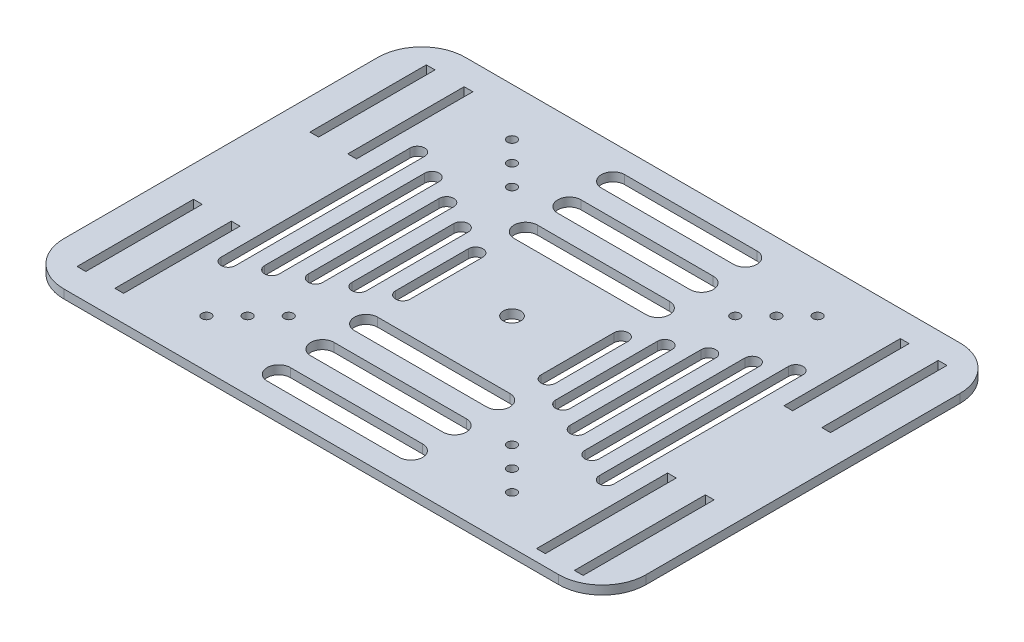
SolidWorks part; units mm, degrees
ref_plane "前视基准面" through (0, 0, 0) normal (0, 0, 1) x (1, 0, 0)
ref_plane "上视基准面" through (0, 0, 0) normal (0, 1, 0) x (1, 0, 0)
ref_plane "右视基准面" through (0, 0, 0) normal (1, 0, 0) x (0, 0, -1)
sketch "草图2" plane through (0, 0, 0) normal (0, 1, 0) x (1, 0, 0)
  line L0 (100, 100) -> (100, -100)
  line L1 (100, 100) -> (-100, 100) construction
  line L2 (100, -100) -> (-100, -100) construction
  line L3 (-100, 100) -> (-100, -100)
  line L4 (100, 100) -> (-100, -100) construction
  line L5 (100, -100) -> (-100, 100) construction
  line L6 (0, 65) -> (0, -65) construction
  line L7 (-68.9429, -68.9429) -> (68.9429, 68.9429) construction
  line L8 (-68.9429, 68.9429) -> (68.9429, -68.9429) construction
  line L9 (68.9429, 68.9429) -> (68.9429, -68.9429) construction
  line L10 (-68.9429, -68.9429) -> (-68.9429, 68.9429) construction
  line L11 (68.9429, 68.9429) -> (-68.9429, 68.9429)
  line L12 (-68.9429, -68.9429) -> (68.9429, -68.9429)
  line L13 (68.9429, 0) -> (81.4429, 0)
  line L14 (81.4429, 10) -> (81.4429, -10) construction
  line L15 (81.4429, 0) -> (76.4429, 0) construction
  line L16 (86.4429, -10) -> (89.4429, -10) construction
  line L17 (76.4429, 10) -> (73.4429, 10) construction
  line L18 (76.4429, 10) -> (76.4429, -10) construction
  line L19 (76.4429, -10) -> (73.4429, -10) construction
  line L20 (73.4429, 10) -> (73.4429, -10) construction
  line L21 (89.4429, 10) -> (89.4429, -10) construction
  line L22 (86.4429, 10) -> (86.4429, -10) construction
  line L23 (86.4429, 10) -> (89.4429, 10) construction
  line L24 (0, -65) -> (0, -100)
  line L25 (-60, -82.5) -> (60, -82.5) construction
  line L34 (-60, 82.5) -> (60, 82.5) construction
  line L35 (-81.4429, -10) -> (-81.4429, 10) construction
  line L36 (-81.4429, 0) -> (-76.4429, 0) construction
  line L37 (-86.4429, 10) -> (-89.4429, 10) construction
  line L38 (-76.4429, -10) -> (-73.4429, -10) construction
  line L39 (-76.4429, -10) -> (-76.4429, 10) construction
  line L40 (-76.4429, 10) -> (-73.4429, 10) construction
  line L41 (-73.4429, -10) -> (-73.4429, 10) construction
  line L42 (-89.4429, -10) -> (-89.4429, 10) construction
  line L43 (-86.4429, -10) -> (-86.4429, 10) construction
  line L44 (-86.4429, -10) -> (-89.4429, -10) construction
  line L45 (-60, 73.5) -> (60, 73.5) construction
  line L46 (-60, -73.5) -> (60, -73.5) construction
  line L47 (-60, -91.5) -> (60, -91.5) construction
  line L57 (0, 65) -> (73.4429, 65) construction
  line L58 (73.4429, 85) -> (73.4429, 45) construction
  line L59 (73.4429, 85) -> (76.4429, 85) construction
  line L60 (76.4429, 85) -> (76.4429, 45) construction
  line L61 (76.4429, 45) -> (73.4429, 45) construction
  line L62 (86.4429, 45) -> (89.4429, 45) construction
  line L63 (86.4429, 85) -> (86.4429, 45) construction
  line L64 (89.4429, 85) -> (86.4429, 85) construction
  line L65 (89.4429, 85) -> (89.4429, 45) construction
  line L66 (73.4429, -85) -> (73.4429, -45) construction
  line L67 (89.4429, -85) -> (89.4429, -45) construction
  line L68 (89.4429, -85) -> (86.4429, -85) construction
  line L69 (86.4429, -85) -> (86.4429, -45) construction
  line L70 (86.4429, -45) -> (89.4429, -45) construction
  line L71 (76.4429, -45) -> (73.4429, -45) construction
  line L72 (76.4429, -85) -> (76.4429, -45) construction
  line L73 (73.4429, -85) -> (76.4429, -85) construction
  line L74 (-73.4429, -85) -> (-76.4429, -85) construction
  line L75 (-76.4429, -85) -> (-76.4429, -45) construction
  line L76 (-76.4429, -45) -> (-73.4429, -45) construction
  line L77 (-86.4429, -45) -> (-89.4429, -45) construction
  line L78 (-86.4429, -85) -> (-86.4429, -45) construction
  line L79 (-89.4429, -85) -> (-86.4429, -85) construction
  line L80 (-89.4429, -85) -> (-89.4429, -45) construction
  line L81 (-73.4429, -85) -> (-73.4429, -45) construction
  line L82 (-89.4429, 85) -> (-89.4429, 45) construction
  line L83 (-89.4429, 85) -> (-86.4429, 85) construction
  line L84 (-86.4429, 85) -> (-86.4429, 45) construction
  line L85 (-86.4429, 45) -> (-89.4429, 45) construction
  line L86 (-76.4429, 45) -> (-73.4429, 45) construction
  line L87 (-76.4429, 85) -> (-76.4429, 45) construction
  line L88 (-73.4429, 85) -> (-76.4429, 85) construction
  line L89 (-73.4429, 85) -> (-73.4429, 45) construction
  line L90 (22.7145, 27.4289) -> (-22.7145, 27.4289) construction
  line L91 (22.7145, 23.4289) -> (-22.7145, 23.4289)
  line L96 (-45.4289, 45.4289) -> (0, 45.4289)
  line L99 (22.7145, 31.4289) -> (-22.7145, 31.4289)
  line L102 (22.7145, 42.4289) -> (-22.7145, 42.4289) construction
  line L108 (0, 0) -> (-52.5, 0)
  line L111 (-10, 86.4429) -> (10, 86.4429) [skipped]
  line L112 (-10, 81.4429) -> (10, 81.4429) [skipped]
  line L113 (0, 81.4429) -> (0, 76.4429) [skipped]
  line L114 (10, 86.4429) -> (10, 89.4429) [skipped]
  line L115 (-10, 76.4429) -> (-10, 73.4429) [skipped]
  line L116 (-10, 76.4429) -> (10, 76.4429) [skipped]
  line L117 (10, 76.4429) -> (10, 73.4429) [skipped]
  line L118 (-10, 73.4429) -> (10, 73.4429) [skipped]
  line L119 (-10, 89.4429) -> (10, 89.4429) [skipped]
  line L120 (-10, 86.4429) -> (-10, 89.4429) [skipped]
  line L121 (0, 68.9429) -> (0, 81.4429) construction
  line L122 (10, -81.4429) -> (-10, -81.4429) [skipped]
  line L123 (0, -81.4429) -> (0, -76.4429) [skipped]
  line L124 (-10, -86.4429) -> (-10, -89.4429) [skipped]
  line L125 (10, -76.4429) -> (-10, -76.4429) [skipped]
  line L126 (10, -89.4429) -> (-10, -89.4429) [skipped]
  line L127 (10, -86.4429) -> (-10, -86.4429) [skipped]
  line L128 (10, -86.4429) -> (10, -89.4429) [skipped]
  line L129 (10, -76.4429) -> (10, -73.4429) [skipped]
  line L130 (-10, -76.4429) -> (-10, -73.4429) [skipped]
  line L131 (10, -73.4429) -> (-10, -73.4429) [skipped]
  line L132 (0, -68.9429) -> (0, -81.4429) construction
  line L135 (22.7145, 38.4289) -> (-22.7145, 38.4289)
  line L137 (-52.5, 0) -> (-52.5, 52.5)
  line L147 (22.7145, 46.4289) -> (-22.7145, 46.4289)
  line L156 (22.7145, 57.4289) -> (-22.7145, 57.4289) construction
  line L165 (22.7145, 53.4289) -> (-22.7145, 53.4289)
  line L170 (0, 0) -> (25, 0)
  line L171 (25, 0) -> (25, 25)
  line L172 (25, 0) -> (35, 0)
  line L177 (35, 0) -> (45, 0)
  line L180 (45, 0) -> (55, 0)
  line L183 (55, 0) -> (65, 0)
  line L184 (65, 0) -> (65, 65)
  line L185 (55, 0) -> (55, 55)
  line L186 (45, 0) -> (45, 45)
  line L187 (35, 0) -> (35, 35)
  line L188 (25, -12.5) -> (25, 12.5) construction
  line L189 (22.5, -12.5) -> (22.5, 12.5)
  line L190 (27.5, -12.5) -> (27.5, 12.5)
  line L191 (35, -17.5) -> (35, 17.5) construction
  line L192 (32.5, -17.5) -> (32.5, 17.5)
  line L193 (37.5, -17.5) -> (37.5, 17.5)
  line L194 (45, -22.5) -> (45, 22.5) construction
  line L195 (42.5, -22.5) -> (42.5, 22.5)
  line L196 (47.5, -22.5) -> (47.5, 22.5)
  line L197 (55, -27.5) -> (55, 27.5) construction
  line L198 (52.5, -27.5) -> (52.5, 27.5)
  line L199 (57.5, -27.5) -> (57.5, 27.5)
  line L200 (65, -32.5) -> (65, 32.5) construction
  line L201 (62.5, -32.5) -> (62.5, 32.5)
  line L202 (67.5, -32.5) -> (67.5, 32.5)
  line L203 (-25, -12.5) -> (-25, 12.5) construction
  line L204 (-22.5, -12.5) -> (-22.5, 12.5)
  line L205 (-27.5, -12.5) -> (-27.5, 12.5)
  line L206 (-35, -17.5) -> (-35, 17.5) construction
  line L207 (-32.5, -17.5) -> (-32.5, 17.5)
  line L208 (-37.5, -17.5) -> (-37.5, 17.5)
  line L209 (-45, -22.5) -> (-45, 22.5) construction
  line L210 (-42.5, -22.5) -> (-42.5, 22.5)
  line L211 (-47.5, -22.5) -> (-47.5, 22.5)
  line L212 (-55, -27.5) -> (-55, 27.5) construction
  line L213 (-52.5, -27.5) -> (-52.5, 27.5)
  line L214 (-57.5, -27.5) -> (-57.5, 27.5)
  line L215 (-65, -32.5) -> (-65, 32.5) construction
  line L216 (-62.5, -32.5) -> (-62.5, 32.5)
  line L217 (-67.5, -32.5) -> (-67.5, 32.5)
  line L218 (-68.9429, 0) -> (-81.4429, 0) construction
  line L219 (-60, 91.5) -> (60, 91.5) construction
  line L220 (-89.4429, 45) -> (-89.4429, 20)
  line L221 (-89.4429, 20) -> (-86.4429, 20)
  line L226 (-68.9429, 68.9429) -> (-100, 68.9429)
  line L227 (68.9429, 68.9429) -> (100, 68.9429)
  line L228 (-68.9429, -68.9429) -> (-100, -68.9429)
  line L229 (68.9429, -68.9429) -> (100, -68.9429)
  line L248 (73.4429, -65) -> (76.4429, -65)
  line L249 (73.4429, -45) -> (73.4429, -65)
  line L250 (73.4429, -45) -> (73.4429, -20)
  line L251 (76.4429, -65) -> (76.4429, -20)
  line L252 (73.4429, -20) -> (76.4429, -20)
  line L253 (89.4429, -65) -> (86.4429, -65)
  line L254 (89.4429, -45) -> (89.4429, -65)
  line L255 (86.4429, -65) -> (86.4429, -20)
  line L256 (89.4429, -45) -> (89.4429, -20)
  line L257 (89.4429, -20) -> (86.4429, -20)
  line L268 (22.7145, 61.4289) -> (-22.7145, 61.4289)
  line L269 (22.7145, -57.4289) -> (-22.7145, -57.4289) construction
  line L270 (22.7145, -53.4289) -> (-22.7145, -53.4289)
  line L271 (22.7145, -61.4289) -> (-22.7145, -61.4289)
  line L272 (22.7145, -42.4289) -> (-22.7145, -42.4289) construction
  line L273 (22.7145, -38.4289) -> (-22.7145, -38.4289)
  line L274 (22.7145, -46.4289) -> (-22.7145, -46.4289)
  line L275 (22.7145, -27.4289) -> (-22.7145, -27.4289) construction
  line L276 (22.7145, -23.4289) -> (-22.7145, -23.4289)
  line L277 (22.7145, -31.4289) -> (-22.7145, -31.4289)
  line L278 (-89.4429, 45) -> (-89.4429, 60)
  line L279 (-89.4429, 60) -> (-86.4429, 60)
  line L280 (-86.4429, 60) -> (-86.4429, 20)
  line L281 (-73.4429, 20) -> (-76.4429, 20)
  line L282 (-73.4429, 45) -> (-73.4429, 20)
  line L283 (-73.4429, 45) -> (-73.4429, 60)
  line L284 (-76.4429, 60) -> (-76.4429, 20)
  line L285 (-73.4429, 60) -> (-76.4429, 60)
  line L286 (-73.4429, -20) -> (-76.4429, -20)
  line L287 (-73.4429, -45) -> (-73.4429, -20)
  line L288 (-73.4429, -45) -> (-73.4429, -60)
  line L289 (-76.4429, -60) -> (-76.4429, -20)
  line L290 (-73.4429, -60) -> (-76.4429, -60)
  line L291 (-89.4429, -20) -> (-86.4429, -20)
  line L292 (-89.4429, -45) -> (-89.4429, -20)
  line L293 (-86.4429, -60) -> (-86.4429, -20)
  line L294 (-89.4429, -45) -> (-89.4429, -60)
  line L295 (-89.4429, -60) -> (-86.4429, -60)
  line L296 (73.4429, -60) -> (76.4429, -60)
  line L297 (89.4429, -60) -> (86.4429, -60)
  line L298 (73.4429, -45) -> (73.4429, -60)
  line L299 (89.4429, -45) -> (89.4429, -60)
  line L300 (73.4429, -45) -> (73.4429, -20)
  line L301 (76.4429, -60) -> (76.4429, -20)
  line L302 (86.4429, -60) -> (86.4429, -20)
  line L303 (89.4429, -45) -> (89.4429, -20)
  line L304 (73.4429, -20) -> (76.4429, -20)
  line L305 (89.4429, -20) -> (86.4429, -20)
  line L306 (73.4429, 20) -> (76.4429, 20)
  line L307 (73.4429, 45) -> (73.4429, 20)
  line L308 (73.4429, 45) -> (73.4429, 60)
  line L309 (76.4429, 60) -> (76.4429, 20)
  line L310 (73.4429, 60) -> (76.4429, 60)
  line L311 (89.4429, 20) -> (86.4429, 20)
  line L312 (89.4429, 45) -> (89.4429, 20)
  line L313 (86.4429, 60) -> (86.4429, 20)
  line L314 (89.4429, 45) -> (89.4429, 60)
  line L315 (89.4429, 60) -> (86.4429, 60)
  arc A14 (-60, -73.5) -> (-60, -91.5) centre (-60, -82.5) ccw construction
  arc A15 (60, -91.5) -> (60, -73.5) centre (60, -82.5) ccw construction
  circle A18 centre (-52.5, 52.5) radius 1.6
  circle A19 centre (-45.4289, 45.4289) radius 1.6
  circle A20 centre (-38.3579, 38.3579) radius 1.6
  circle A21 centre (52.5, 52.5) radius 1.6
  circle A22 centre (45.4289, 45.4289) radius 1.6
  circle A23 centre (38.3579, 38.3579) radius 1.6
  circle A24 centre (52.5, -52.5) radius 1.6
  circle A25 centre (45.4289, -45.4289) radius 1.6
  circle A26 centre (38.3579, -38.3579) radius 1.6
  circle A27 centre (-52.5, -52.5) radius 1.6
  circle A28 centre (-45.4289, -45.4289) radius 1.6
  circle A29 centre (-38.3579, -38.3579) radius 1.6
  circle A54 centre (0, 0) radius 12.5 construction
  arc A55 (22.7145, 23.4289) -> (22.7145, 31.4289) centre (22.7145, 27.4289) ccw
  arc A56 (-22.7145, 31.4289) -> (-22.7145, 23.4289) centre (-22.7145, 27.4289) ccw
  arc A73 (22.5, -12.5) -> (27.5, -12.5) centre (25, -12.5) ccw
  arc A74 (27.5, 12.5) -> (22.5, 12.5) centre (25, 12.5) ccw
  arc A75 (32.5, -17.5) -> (37.5, -17.5) centre (35, -17.5) ccw
  arc A76 (37.5, 17.5) -> (32.5, 17.5) centre (35, 17.5) ccw
  arc A77 (42.5, -22.5) -> (47.5, -22.5) centre (45, -22.5) ccw
  arc A78 (47.5, 22.5) -> (42.5, 22.5) centre (45, 22.5) ccw
  arc A79 (52.5, -27.5) -> (57.5, -27.5) centre (55, -27.5) ccw
  arc A80 (57.5, 27.5) -> (52.5, 27.5) centre (55, 27.5) ccw
  arc A81 (62.5, -32.5) -> (67.5, -32.5) centre (65, -32.5) ccw
  arc A82 (67.5, 32.5) -> (62.5, 32.5) centre (65, 32.5) ccw
  arc A83 (-22.5, -12.5) -> (-27.5, -12.5) centre (-25, -12.5) cw
  arc A84 (-27.5, 12.5) -> (-22.5, 12.5) centre (-25, 12.5) cw
  arc A85 (-32.5, -17.5) -> (-37.5, -17.5) centre (-35, -17.5) cw
  arc A86 (-37.5, 17.5) -> (-32.5, 17.5) centre (-35, 17.5) cw
  arc A87 (-42.5, -22.5) -> (-47.5, -22.5) centre (-45, -22.5) cw
  arc A88 (-47.5, 22.5) -> (-42.5, 22.5) centre (-45, 22.5) cw
  arc A89 (-52.5, -27.5) -> (-57.5, -27.5) centre (-55, -27.5) cw
  arc A90 (-57.5, 27.5) -> (-52.5, 27.5) centre (-55, 27.5) cw
  arc A91 (-62.5, -32.5) -> (-67.5, -32.5) centre (-65, -32.5) cw
  arc A92 (-67.5, 32.5) -> (-62.5, 32.5) centre (-65, 32.5) cw
  arc A106 (-60, 73.5) -> (-60, 91.5) centre (-60, 82.5) cw construction
  arc A107 (60, 91.5) -> (60, 73.5) centre (60, 82.5) cw construction
  circle A112 centre (0, 0) radius 3
  arc A113 (22.7145, 38.4289) -> (22.7145, 46.4289) centre (22.7145, 42.4289) ccw
  arc A114 (-22.7145, 46.4289) -> (-22.7145, 38.4289) centre (-22.7145, 42.4289) ccw
  arc A115 (22.7145, 53.4289) -> (22.7145, 61.4289) centre (22.7145, 57.4289) ccw
  arc A116 (-22.7145, 61.4289) -> (-22.7145, 53.4289) centre (-22.7145, 57.4289) ccw
  arc A117 (22.7145, -53.4289) -> (22.7145, -61.4289) centre (22.7145, -57.4289) cw
  arc A118 (-22.7145, -61.4289) -> (-22.7145, -53.4289) centre (-22.7145, -57.4289) cw
  arc A119 (22.7145, -38.4289) -> (22.7145, -46.4289) centre (22.7145, -42.4289) cw
  arc A120 (-22.7145, -46.4289) -> (-22.7145, -38.4289) centre (-22.7145, -42.4289) cw
  arc A121 (22.7145, -23.4289) -> (22.7145, -31.4289) centre (22.7145, -27.4289) cw
  arc A122 (-22.7145, -31.4289) -> (-22.7145, -23.4289) centre (-22.7145, -27.4289) cw
  point P1 (0, 0)
  point P4 (0, 0)
  point P7 (0, 0)
  point P15 (0, 0)
  point P20 (81.4429, 0)
  point P35 (0, -81.4429)
  point P38 (0, -82.5)
  point P43 (0, 82.5)
  point P51 (-81.4429, 0)
  point P62 (0, 81.4429)
  point P74 (0, 0)
  point P76 (73.4429, 65)
  point P82 (89.4429, 65)
  point P91 (89.4429, -65)
  point P109 (-89.4429, 65)
  point P110 (-73.4429, 65)
  point P115 (0, 27.4289)
  point P136 (0, 0)
  point P139 (0, 42.4289)
  point P146 (0, 57.4289)
  point P152 (0, -57.4289)
  point P159 (0, -42.4289)
  point P210 (0, -27.4289)
  point P227 (25, 0)
  point P233 (35, 0)
  point P241 (45, 0)
  point P247 (55, 0)
  point P254 (65, 0)
  point P261 (0, 0)
  point P263 (-25, 0)
  point P270 (-35, 0)
  point P277 (-45, 0)
  point P284 (-55, 0)
  point P291 (-65, 0)
  dimension "D10" = 3.2
  dimension "D15" = 25
  dimension "D14" = 3
  dimension "D22" = 6
  dimension "D23" = 25
  dimension "D1" = 200
  dimension "D2" = 200
  dimension "D3" = 12.5
  dimension "D4" = 10
  dimension "D5" = 5
  dimension "D6" = 20
  dimension "D7" = 3
  dimension "D8" = 4
  dimension "D9" = 20
  dimension "D12" = 52.5
  dimension "D13" = 4
  dimension "D17" = 25
  dimension "D18" = 10
  dimension "D19" = 10
  dimension "D20" = 10
  dimension "D21" = 10
  dimension "D16" = 15
  dimension "D11" = 3
extrude "凸台-拉伸1" add sketch "草图2" along normal blind 3
fillet "圆角1" radius 15 4 edges at (-100, 1.5, -68.9429) (100, 1.5, -68.9429) (100, 1.5, 68.9429) (-100, 1.5, 68.9429)
